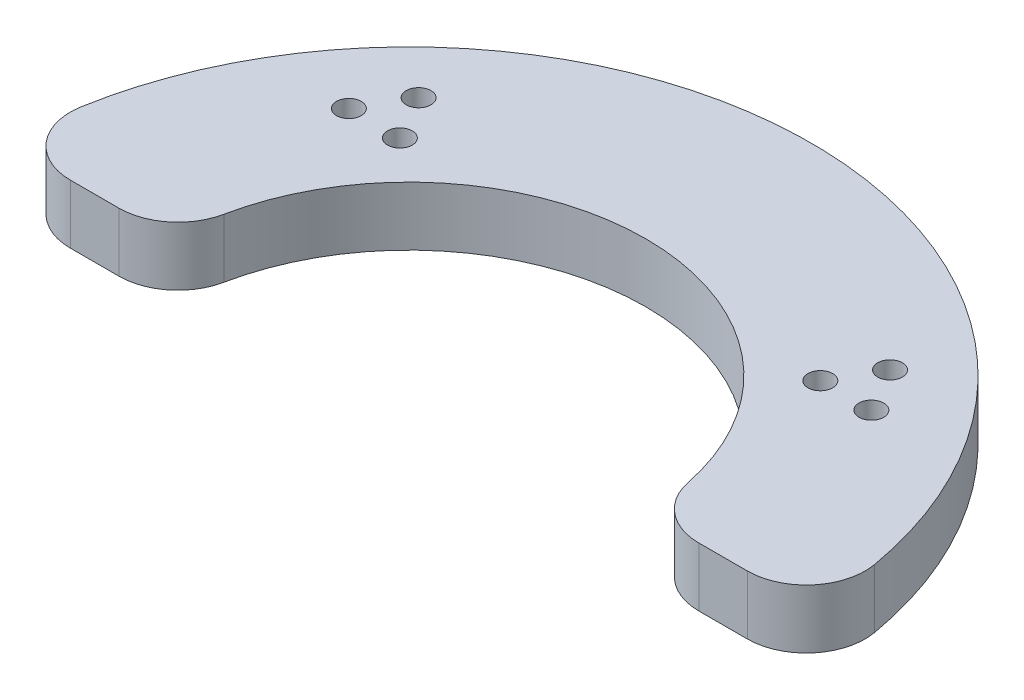
SolidWorks part; units mm, degrees
ref_plane "前视基准面" through (0, 0, 0) normal (0, 0, 1) x (1, 0, 0)
ref_plane "上视基准面" through (0, 0, 0) normal (0, 1, 0) x (1, 0, 0)
ref_plane "右视基准面" through (0, 0, 0) normal (1, 0, 0) x (0, 0, -1)
sketch "草图2" plane through (0, 0, 0) normal (0, 1, 0) x (1, 0, 0)
  line L0 (0, 79.3795) -> (0, 0) construction
  line L1 (0, 0) -> (79.3795, 0) construction
  line L2 (0, 0) -> (40, 36.6532) construction
  circle A0 centre (40, 36.6532) radius 10.05
  circle A1 centre (0, 0) radius 44.2037 construction
  circle A2 centre (0, 0) radius 64.3037 construction
  circle A3 centre (0, 0) radius 68.3037
  circle A4 centre (0, 0) radius 40.2037
  circle A5 centre (-40, 36.6532) radius 10.05
  dimension "D1" = 20.1
  dimension "D2" = 40
  dimension "D3" = 42.5
  dimension "D4" = 4
  dimension "D5" = 4
extrude "凸台-拉伸1" add sketch "草图2" along normal blind 10
sketch "草图3" plane through (0, 10, 0) normal (0, 1, 0) x (1, 0, 0)
  circle A0 centre (-40, 36.6532) radius 10.05
  circle A1 centre (40, 36.6532) radius 10.05
extrude "凸台-拉伸2" add sketch "草图3" against normal blind 5
sketch "草图4" plane through (0, 0, 0) normal (0, -1, 0) x (-1, 0, 0)
  line L1 (-132.8688, 0) -> (147.4224, 0)
  line L2 (-132.8688, 0) -> (-132.8688, -106.8495)
  line L3 (-132.8688, -106.8495) -> (147.4224, -106.8495)
  line L4 (147.4224, 0) -> (147.4224, -106.8495)
extrude "切除-拉伸2" cut sketch "草图4" against normal blind 45
sketch "草图5" plane through (0, 5, 0) normal (0, -1, 0) x (-1, 0, 0)
  line L1 (-40, 41.6532) -> (-44.3301, 34.1532) construction
  line L2 (-44.3301, 34.1532) -> (-35.6699, 34.1532) construction
  line L3 (-35.6699, 34.1532) -> (-40, 41.6532) construction
  circle A0 centre (-40, 36.6532) radius 5 construction
  circle A1 centre (-40, 41.6532) radius 2.1
  circle A2 centre (-35.6699, 34.1532) radius 2.1
  circle A3 centre (-44.3301, 34.1532) radius 2.1
  dimension "D1" = 10
  dimension "D2" = 4.2
  dimension "D3" = 4.2
  dimension "D4" = 4.2
extrude "切除-拉伸3" cut sketch "草图5" against normal blind 45
mirror "镜向1" about plane through (0, 0, 0) normal (1, 0, 0) of "切除-拉伸3"
fillet "圆角1" radius 10 4 edges at (68.3037, 5, 0) (-68.3037, 5, 0) (40.2037, 5, 0) (-40.2037, 5, 0)
